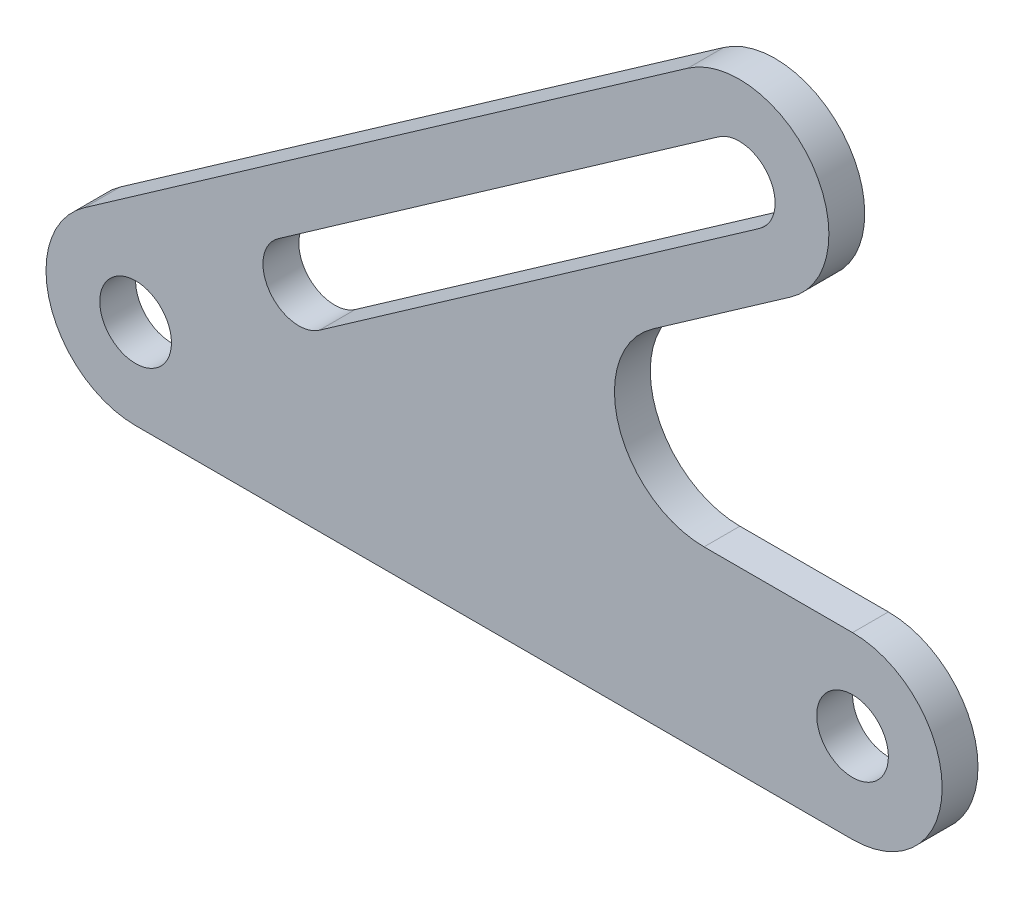
SolidWorks part; units mm, degrees
ref_plane "Front Plane" through (0, 0, 0) normal (0, 0, 1) x (1, 0, 0)
ref_plane "Top Plane" through (0, 0, 0) normal (0, 1, 0) x (1, 0, 0)
ref_plane "Right Plane" through (0, 0, 0) normal (1, 0, 0) x (0, 0, -1)
sketch "Sketch1" plane through (0, 0, 0) normal (0, 0, 1) x (1, 0, 0)
  line L0 (0, 0) -> (80, 0) construction
  line L1 (80, 0) -> (67.3616, 47.1671) construction
  line L2 (67.3616, 47.1671) -> (0, 0) construction
  line L3 (0, 0) -> (67.3616, 47.1671) construction
  line L4 (-5.7358, 8.1915) -> (61.6258, 55.3586)
  line L5 (5.7358, -8.1915) -> (73.0974, 38.9756)
  line L6 (0, 0) -> (80, 0) construction
  line L7 (0, 10) -> (80, 10)
  line L8 (0, -10) -> (80, -10)
  arc A0 (-5.7358, 8.1915) -> (5.7358, -8.1915) centre (0, 0) ccw
  arc A1 (73.0974, 38.9756) -> (61.6258, 55.3586) centre (67.3616, 47.1671) ccw
  arc A2 (0, 10) -> (0, -10) centre (0, 0) ccw
  arc A3 (80, -10) -> (80, 10) centre (80, 0) ccw
  point P3 (33.6808, 23.5836)
  point P9 (40, 0)
  dimension "D4" = 10
  dimension "D5" = 10
  dimension "D1" = 80
  dimension "D2" = 75
  dimension "D3" = 35
extrude "Boss-Extrude1" add sketch "Sketch1" along normal mid plane 4 contours A2 L7 L5 A1 L4 | L7 A2 A0 L5 | L8 A3 L7 L5 A0
sketch "Sketch2" plane through (0, 0, 0) normal (0, 0, 1) x (1, 0, 0)
  line L0 (67.3616, 47.1671) -> (18.2125, 12.7525) construction
  line L1 (69.6559, 43.8905) -> (20.5068, 9.4759)
  line L2 (65.0673, 50.4437) -> (15.9182, 16.0291)
  line L4 (61.6258, 55.3586) -> (-5.7358, 8.1915)
  line L5 (0, -10) -> (80, -10)
  line L6 (80, 10) -> (31.7159, 10)
  line L7 (31.7159, 10) -> (73.0974, 38.9756)
  line L8 (61.6258, 55.3586) -> (-5.7358, 8.1915)
  line L9 (0, -10) -> (80, -10)
  line L10 (80, 10) -> (31.7159, 10)
  line L11 (31.7159, 10) -> (73.0974, 38.9756)
  arc A0 (69.6559, 43.8905) -> (65.0673, 50.4437) centre (67.3616, 47.1671) ccw
  arc A1 (15.9182, 16.0291) -> (20.5068, 9.4759) centre (18.2125, 12.7525) ccw
  circle A2 centre (0, 0) radius 4
  arc A3 (-5.7358, 8.1915) -> (0, -10) centre (0, 0) ccw
  arc A4 (80, -10) -> (80, 10) centre (80, 0) ccw
  arc A5 (73.0974, 38.9756) -> (61.6258, 55.3586) centre (67.3616, 47.1671) ccw
  arc A6 (-5.7358, 8.1915) -> (0, -10) centre (0, 0) ccw
  arc A7 (80, -10) -> (80, 10) centre (80, 0) ccw
  arc A8 (73.0974, 38.9756) -> (61.6258, 55.3586) centre (67.3616, 47.1671) ccw
  circle A9 centre (80, 0) radius 4
  point P7 (42.7871, 29.9598)
  dimension "D2" = 4
  dimension "D3" = 60
  dimension "D4" = 8
  dimension "D1" = 0
extrude "Cut-Extrude1" cut sketch "Sketch2" against normal through all and the other way blind 4 contours A9 | L2 A1 L1 A0 | A2
fillet "Fillet1" radius 10 1 edges at (31.7159, 10, 0)
